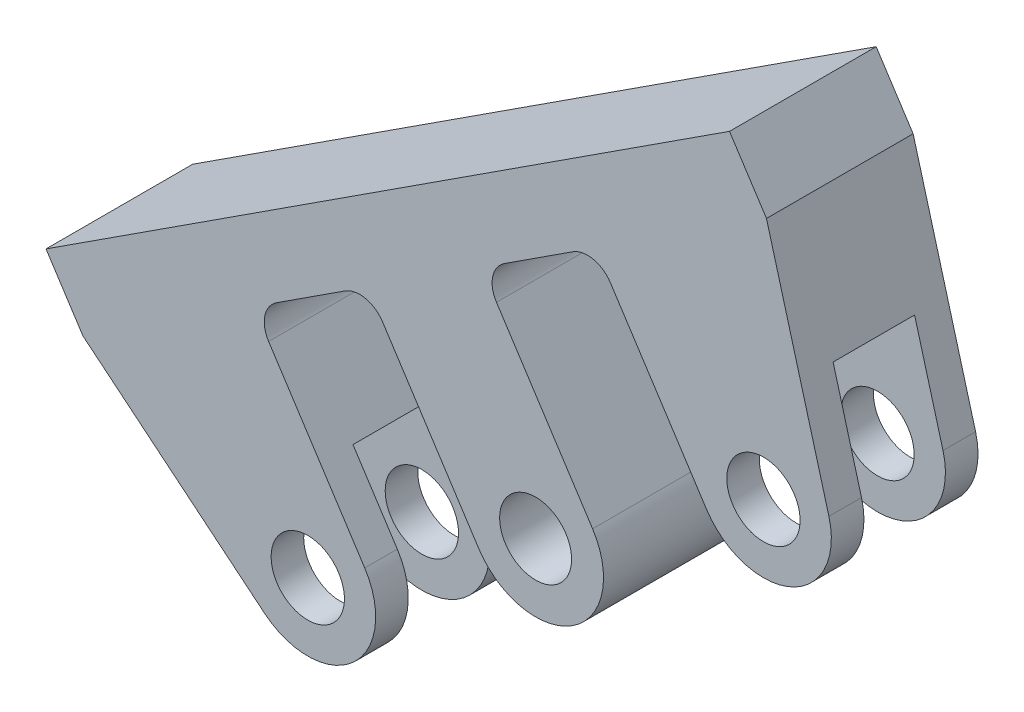
SolidWorks part; units mm, degrees
ref_plane "Front Plane" through (0, 0, 0) normal (0, 0, 1) x (1, 0, 0)
ref_plane "Top Plane" through (0, 0, 0) normal (0, 1, 0) x (1, 0, 0)
ref_plane "Right Plane" through (0, 0, 0) normal (1, 0, 0) x (0, 0, -1)
sketch "Sketch1" plane through (0, 0, 0) normal (0, 0, 1) x (1, 0, 0)
  line L0 (-3.1734, 28.2202) -> (-67.0938, -13.2602)
  line L1 (-3.1734, 28.2202) -> (14.1101, 1.5867)
  line L2 (-67.0938, -13.2602) -> (-49.8103, -39.8937)
  line L3 (14.1101, 1.5867) -> (-49.8103, -39.8937)
  circle A0 centre (0, 0) radius 3.175
  circle A1 centre (-42.6136, -27.6536) radius 3.175
  circle A2 centre (-21.3068, -13.8268) radius 3.1115
  dimension "D1" = 6.35
  dimension "D3" = 6.223
  dimension "D2" = 31.75
extrude "Boss-Extrude1" add sketch "Sketch1" against normal blind 50.8
ref_plane "Plane1" through (0, 0, -25.4) normal (0, 0, 1) x (1, 0, 0)
sketch "Sketch2" plane through (0, 0, -25.4) normal (0, 0, 1) x (1, 0, 0)
  line L0 (-42.6136, -27.6536) -> (-36.1082, -14.3481) construction
  line L1 (-36.1082, -14.3481) -> (-57.4151, -28.1749)
  line L2 (-67.0938, -13.2602) -> (-49.8103, -39.8937) construction
  line L3 (0, 0) -> (-14.8014, -0.5213) construction
  line L4 (-14.8014, -0.5213) -> (6.5054, 13.3054)
  line L5 (14.1101, 1.5867) -> (-3.1734, 28.2202) construction
  line L6 (-57.4151, -28.1749) -> (-49.8103, -39.8937)
  line L7 (-49.8103, -39.8937) -> (-39.1569, -32.9803)
  line L9 (-49.8103, -39.8937) -> (14.1101, 1.5867) construction
  line L10 (6.5054, 13.3054) -> (14.1101, 1.5867)
  line L11 (14.1101, 1.5867) -> (3.4567, -5.3267)
  line L13 (-36.1082, -14.3481) -> (-28.5035, -26.0669)
  line L14 (-28.5035, -26.0669) -> (-39.1569, -32.9803)
  line L15 (-14.8014, -0.5213) -> (-7.1967, -12.2401)
  line L16 (-7.1967, -12.2401) -> (3.4567, -5.3267)
  dimension "D1" = 12.7
  dimension "D2" = 12.7
  dimension "D3" = 13.97
extrude "Cut-Extrude1" cut sketch "Sketch2" against normal mid plane 7.62
sketch "Sketch3" plane through (0, 0, -25.4) normal (0, 0, 1) x (1, 0, 0)
  line L0 (-26.6335, -17.2835) -> (-23.1768, -22.6102)
  line L1 (-49.8103, -39.8937) -> (14.1101, 1.5867) construction
  line L2 (-15.9801, -10.3701) -> (-12.5234, -15.6968)
  line L3 (-23.1768, -22.6102) -> (-12.5234, -15.6968)
  circle A0 centre (-21.3068, -13.8268) radius 6.35
  dimension "D1" = 12.7
extrude "Cut-Extrude2" [suppressed] cut sketch "Sketch3" against normal mid plane 12.7 contours A0 | A0 L3 L2 | A0 L0 L3
sketch "Sketch4" plane through (0, 0, -25.4) normal (0, 0, 1) x (1, 0, 0)
  circle A0 centre (-21.3068, -13.8268) radius 12.7
  dimension "D1" = 25.4
extrude "Cut-Extrude3" [suppressed] cut sketch "Sketch4" against normal mid plane 7.9375
sketch "Sketch7" plane through (0, 0, 0) normal (0, 0, 1) x (1, 0, 0)
  line L0 (-37.2869, -24.1969) -> (-47.657, -8.2168)
  line L1 (-47.657, -8.2168) -> (-37.0036, -1.3034)
  line L2 (-37.0036, -1.3034) -> (-26.6335, -17.2835)
  line L3 (-15.9801, -10.3701) -> (-26.3502, 5.61)
  line L4 (-26.3502, 5.61) -> (-15.6968, 12.5234)
  line L5 (-15.6968, 12.5234) -> (-5.3267, -3.4567)
  line L6 (6.1222, 1.6855) -> (0.2833, 22.8935)
  line L7 (14.1101, 1.5867) -> (-3.1734, 28.2202) construction
  line L9 (-46.6468, -32.5582) -> (-63.6371, -18.5869)
  line L10 (-67.0938, -13.2602) -> (-49.8103, -39.8937) construction
  line L11 (-3.1734, 28.2202) -> (-67.0938, -13.2602) construction
  line L12 (-63.6371, -18.5869) -> (-49.8103, -39.8937)
  line L13 (-49.8103, -39.8937) -> (14.1101, 1.5867)
  line L14 (14.1101, 1.5867) -> (0.2833, 22.8935)
  circle A0 centre (-42.6136, -27.6536) radius 6.35
  circle A1 centre (-21.3068, -13.8268) radius 6.35
  circle A2 centre (0, 0) radius 6.35
  line M4 (14.1101, 1.5867) -> (-3.1734, 28.2202)
  line M6 (-67.0938, -13.2602) -> (-49.8103, -39.8937)
  line M7 (-49.8103, -39.8937) -> (14.1101, 1.5867)
  dimension "D2" = 12.7
  dimension "D1" = 6.35
extrude "Cut-Extrude6" cut sketch "Sketch7" against normal through all contours A1 L2 L1 L0 A0 L13 | A2 L5 L4 L3 A1 M7 | A2 L13 L6 M4 | A0 L9 M6 M7
ref_plane "Plane2" through (-21.3068, -13.8268, 0) normal (0.8389, 0.5444, 0) x (0, 0, -1)
sketch "Sketch8" plane through (-21.3068, -13.8268, 0) normal (0.8389, 0.5444, 0) x (0, 0, -1)
  line L0 (18.542, -6.35) -> (18.542, 25.4)
  line L1 (0, -6.35) -> (21.59, -6.35) construction
  line L2 (50.8, 25.4) -> (0, 25.4) construction
  line L3 (18.542, 25.4) -> (0, 25.4)
  line L4 (0, 25.4) -> (0, -6.35)
  line L5 (0, -6.35) -> (18.542, -6.35)
  line L6 (32.258, -6.35) -> (32.258, 25.4)
  line L7 (32.258, 25.4) -> (50.8, 25.4)
  line L8 (50.8, 25.4) -> (50.8, -6.35)
  line L9 (50.8, -6.35) -> (32.258, -6.35)
  line L10 (29.21, 0) -> (29.21, -6.35) construction
  line L11 (21.59, -6.35) -> (21.59, 0) construction
  dimension "D1" = 3.048
  dimension "D2" = 3.048
extrude "Cut-Extrude7" cut sketch "Sketch8" against normal through all and the other way through all contours L4 L5 L0 L3 | L9 L8 L7 L6
sketch "Sketch9" plane through (0, 0, -32.258) normal (0, 0, -1) x (-1, 0, 0)
  circle A0 centre (0, 0) radius 3.429
  circle A1 centre (21.3068, -13.8268) radius 3.3655
  circle A2 centre (42.6136, -27.6536) radius 3.429
  circle A3 centre (0, 0) radius 3.175 construction
  circle A4 centre (21.3068, -13.8268) radius 3.1115 construction
  dimension "D1" = 0.254
  dimension "D2" = 0.254
extrude "Cut-Extrude8" cut sketch "Sketch9" against normal through all
fillet "Fillet1" radius 2.54 4 edges at (-47.657, -8.2168, -25.4) (-37.0036, -1.3034, -25.4) (-26.3502, 5.61, -25.4) (-15.6968, 12.5234, -25.4)
